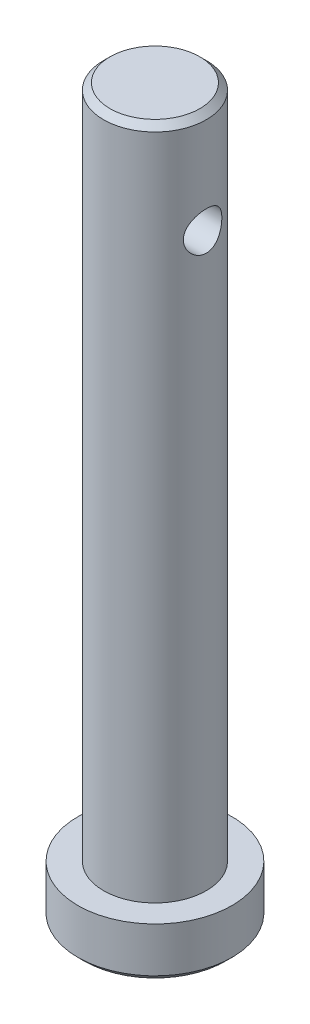
SolidWorks part; units mm, degrees
ref_plane "Front Plane" through (0, 0, 0) normal (1, 0, 0) x (0, 1, 0)
ref_plane "Top Plane" through (0, 0, 0) normal (0, 0, 1) x (0, 1, 0)
ref_plane "Right Plane" through (0, 0, 0) normal (0, 1, 0) x (-1, 0, 0)
sketch "Sketch1" plane through (0, 0, 0) normal (0, 1, 0) x (-1, 0, 0)
  circle A0 centre (0, 0) radius 12
  dimension "D1" = 24
extrude "Boss-Extrude1" add sketch "Sketch1" along normal blind 8
chamfer "Chamfer1" distance 1 angle 45 1 edges at (0, 0, 12)
sketch "Sketch2" plane through (0, 8, 0) normal (0, 1, 0) x (-1, 0, 0)
  circle A0 centre (0, 0) radius 8
  dimension "D1" = 16
extrude "Boss-Extrude2" add sketch "Sketch2" along normal blind 105
chamfer "Chamfer2" distance 1 angle 45 1 edges at (0, 113, 8)
sketch "Sketch3" plane through (0, 0, 0) normal (1, 0, 0) x (0, 1, 0)
  line L0 (8, -8) -> (8, 8) construction
  circle A0 centre (97, 0) radius 3
  point P4 (0, 0)
  dimension "D1" = 6
  dimension "D2" = 89
extrude "Cut-Extrude1" cut sketch "Sketch3" against normal through all both and the other way through all
